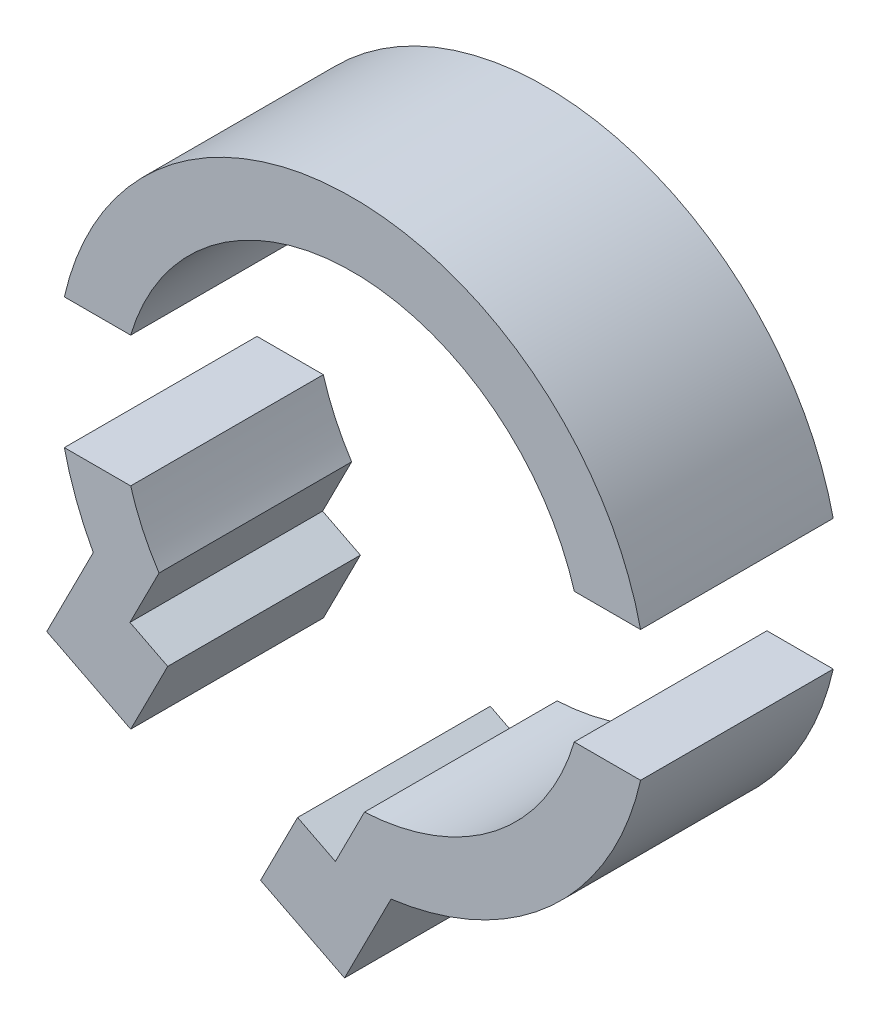
SolidWorks part; units mm, degrees
ref_plane "Front Plane" through (0, 0, 0) normal (0, 0, 1) x (1, 0, 0)
ref_plane "Top Plane" through (0, 0, 0) normal (0, 1, 0) x (1, 0, 0)
ref_plane "Right Plane" through (0, 0, 0) normal (1, 0, 0) x (0, 0, -1)
sketch "Sketch1" plane through (0, 0, 0) normal (0, 0, 1) x (1, 0, 0)
  circle A0 centre (0, 0) radius 23
  circle A1 centre (0, 0) radius 18
  dimension "D1" = 36
  dimension "D2" = 5
extrude "Boss-Extrude1" add sketch "Sketch1" along normal blind 15
sketch "Sketch3" plane through (0, 0, 0) normal (0, 0, 1) x (1, 0, 0)
  line L0 (-23.8014, -18.1679) -> (-0.6174, -29.9366)
  line L1 (-0.6174, -29.9366) -> (3.0037, -22.803)
  line L2 (-23.8014, -18.1679) -> (-20.1803, -11.0343)
  circle A0 centre (0, 0) radius 23 construction
  arc A2 (-20.1803, -11.0343) -> (3.0037, -22.803) centre (0, 0) ccw
  dimension "D1" = 26
  dimension "D2" = 8
  dimension "D3" = 8
extrude "Boss-Extrude2" add sketch "Sketch3" along normal blind 15
sketch "Sketch5" plane through (0, 0, 0) normal (0, 0, 1) x (1, 0, 0)
  line L0 (-15.0623, -9.8553) -> (-17.3255, -14.3138)
  line L1 (-17.3255, -14.3138) -> (-1.3285, -22.4342)
  line L2 (-1.3285, -22.4342) -> (0.9347, -17.9757)
  line L4 (-23.8014, -18.1679) -> (-0.6174, -29.9366) construction
  circle A0 centre (0, 0) radius 18 construction
  arc A1 (0.9347, -17.9757) -> (-15.0623, -9.8553) centre (0, 0) cw
  dimension "D1" = 17.94
  dimension "D2" = 5
  dimension "D3" = 5
extrude "Cut-Extrude1" cut sketch "Sketch5" along normal blind 21
sketch "Sketch6" plane through (0, 0, 0) normal (0, 0, 1) x (1, 0, 0)
  arc A0 (-22.5555, -4.5) -> (-22.5555, 4.5) centre (-21.5191, 0) cw
  circle A1 centre (0, 0) radius 23 construction
  arc A2 (22.5555, -4.5) -> (22.5555, 4.5) centre (21.1441, 0) ccw
  arc A3 (-22.5555, -4.5) -> (-22.5555, 4.5) centre (0, 0) cw
  arc A4 (22.5555, -4.5) -> (22.5555, 4.5) centre (0, 0) ccw
  dimension "D1" = 4.5
  dimension "D2" = 4.5
  dimension "D3" = 4.5
  dimension "D4" = 4.5
extrude "Boss-Extrude3" add sketch "Sketch6" along normal blind 21
sketch "Sketch7" plane through (0, 0, 0) normal (0, 0, 1) x (1, 0, 0)
  circle A0 centre (-21.5, 0) radius 2.2
  circle A1 centre (21.5, 0) radius 2.2
  dimension "D1" = 4.4
  dimension "D2" = 21.5
  dimension "D3" = 21.5
extrude "Cut-Extrude2" cut sketch "Sketch7" along normal blind 21
sketch "Sketch8" plane through (0, 0, 0) normal (0, 0, 1) x (1, 0, 0)
  line L0 (-14.3829, -15.8075) -> (-4.2711, -20.9405)
  line L1 (-17.3255, -14.3138) -> (-1.3285, -22.4342) construction
  line L2 (-4.2711, -20.9405) -> (-5.629, -23.6155)
  line L3 (-5.629, -23.6155) -> (-15.7408, -18.4826)
  line L4 (-15.7408, -18.4826) -> (-14.3829, -15.8075)
  line L5 (-15.0623, -9.8553) -> (-17.3255, -14.3138) construction
  line L6 (-1.3285, -22.4342) -> (0.9347, -17.9757) construction
  dimension "D1" = 3
  dimension "D2" = 3
  dimension "D3" = 3.3
  dimension "D4" = 3.3
extrude "Cut-Extrude3" cut sketch "Sketch8" along normal blind 21
sketch "Sketch9" plane through (0, 0, 0) normal (0, 0, 1) x (1, 0, 0)
  line L1 (-27.3646, -5.0812) -> (27.3646, -5.0812)
  line L2 (-27.3646, -5.0812) -> (-27.3646, 5.0812)
  line L3 (-27.3646, 5.0812) -> (27.3646, 5.0812)
  line L4 (27.3646, -5.0812) -> (27.3646, 5.0812)
  line L5 (-27.3646, -5.0812) -> (27.3646, 5.0812) construction
  line L6 (-27.3646, 5.0812) -> (27.3646, -5.0812) construction
  point P0 (0, 0)
extrude "Cut-Extrude4" cut sketch "Sketch9" along normal blind 21
sketch "Sketch10" plane through (0, 0, 0) normal (0, 0, 1) x (1, 0, 0)
  line L0 (-15.7408, -18.4826) -> (-5.629, -23.6155)
  line L1 (-5.629, -23.6155) -> (-7.1535, -26.6187)
  line L2 (-23.8014, -18.1679) -> (-0.6174, -29.9366) construction
  line L3 (-7.1535, -26.6187) -> (-17.2653, -21.4857)
  line L4 (-17.2653, -21.4857) -> (-15.7408, -18.4826)
extrude "Cut-Extrude5" cut sketch "Sketch10" along normal blind 21
